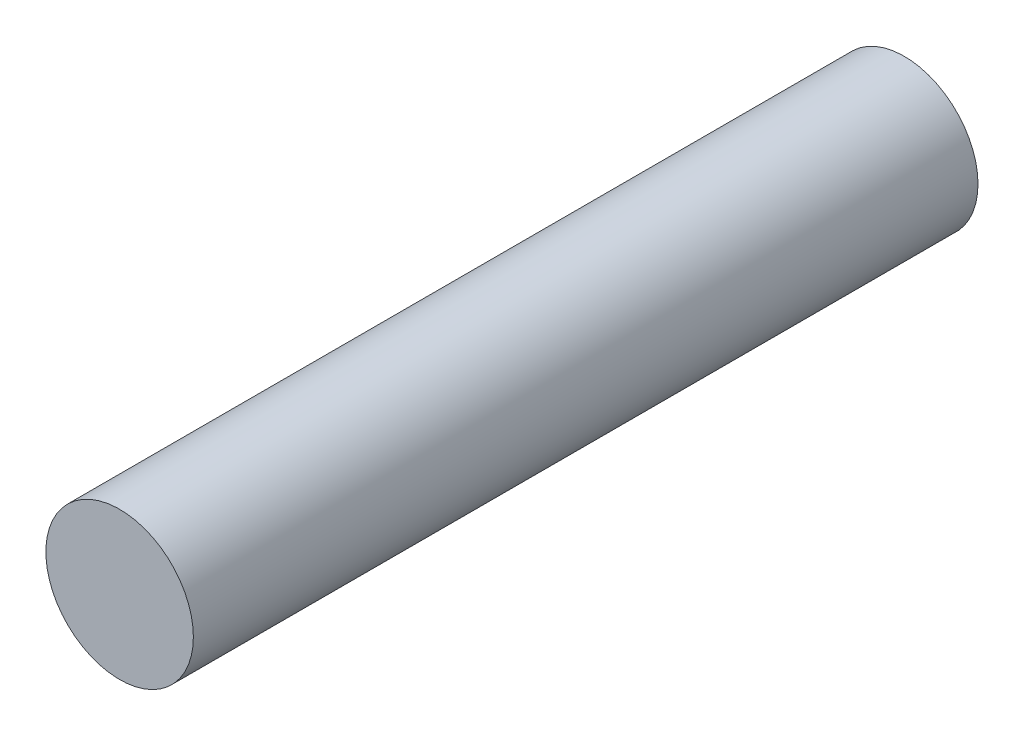
SolidWorks part; units mm, degrees
ref_plane "Plan de face" through (0, 0, 0) normal (0, 0, 1) x (1, 0, 0)
ref_plane "Plan de dessus" through (0, 0, 0) normal (0, 1, 0) x (1, 0, 0)
ref_plane "Plan de droite" through (0, 0, 0) normal (1, 0, 0) x (0, 0, -1)
sketch "Esquisse1" plane through (0, 0, 0) normal (0, 0, 1) x (1, 0, 0)
  circle A0 centre (-3.4816, 1.2064) radius 2.35
  dimension "D1" = 4.7
extrude "Boss.-Extru.1" add sketch "Esquisse1" along normal blind 25
